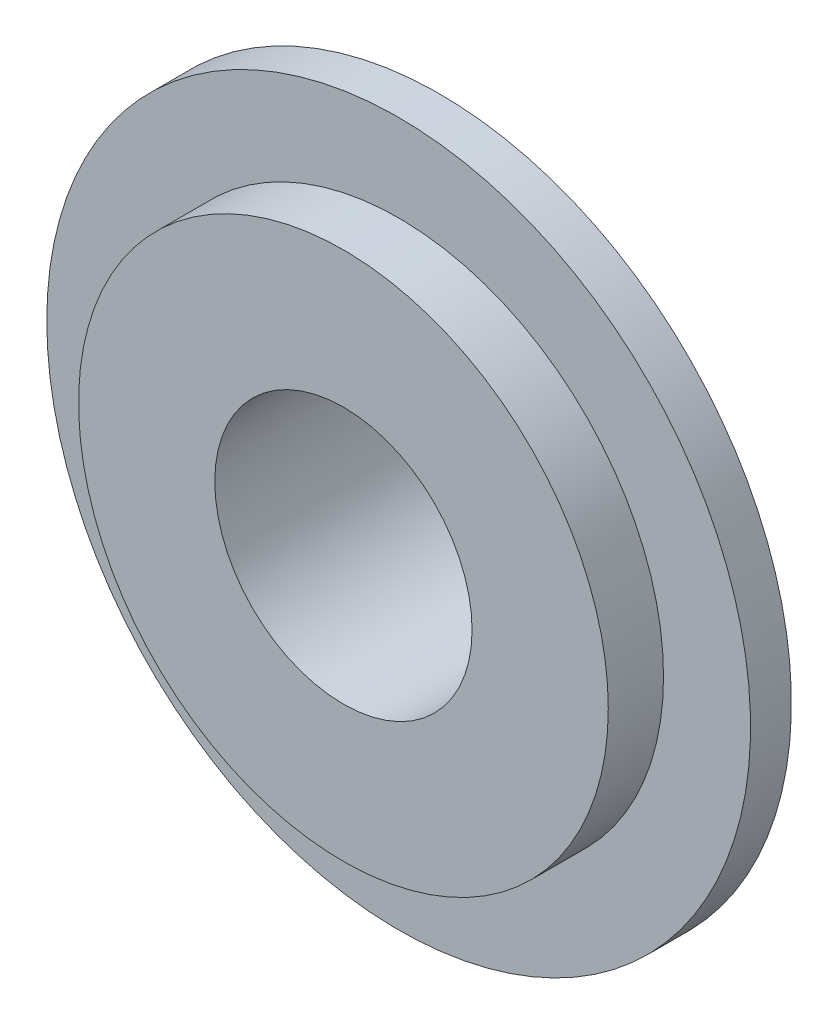
SolidWorks part; units mm, degrees
ref_plane "Front Plane" through (0, 0, 0) normal (0, 0, 1) x (1, 0, 0)
ref_plane "Top Plane" through (0, 0, 0) normal (0, 1, 0) x (1, 0, 0)
ref_plane "Right Plane" through (0, 0, 0) normal (1, 0, 0) x (0, 0, -1)
sketch "Sketch1" plane through (0, 0, 0) normal (0, 0, 1) x (1, 0, 0)
  circle A0 centre (0, 0) radius 8.5
  circle A1 centre (0, 0) radius 17.5
  dimension "D1" = 17
  dimension "D2" = 35
extrude "Boss-Extrude1" add sketch "Sketch1" along normal mid plane 10
sketch "Sketch2" plane through (0, 0, 0) normal (0, 0, 1) x (1, 0, 0)
  circle A0 centre (0, 0) radius 17.5
  circle A1 centre (0, 0) radius 23.25
  dimension "D1" = 46.5
extrude "Boss-Extrude2" add sketch "Sketch2" along normal mid plane 2.7
sketch "Sketch3" plane through (0, 0, -5) normal (0, 0, -1) x (-1, 0, 0)
  circle A0 centre (0, 0) radius 11.587
  circle A1 centre (0, 0) radius 8.5
extrude "Boss-Extrude3" add sketch "Sketch3" along normal blind 2.7
